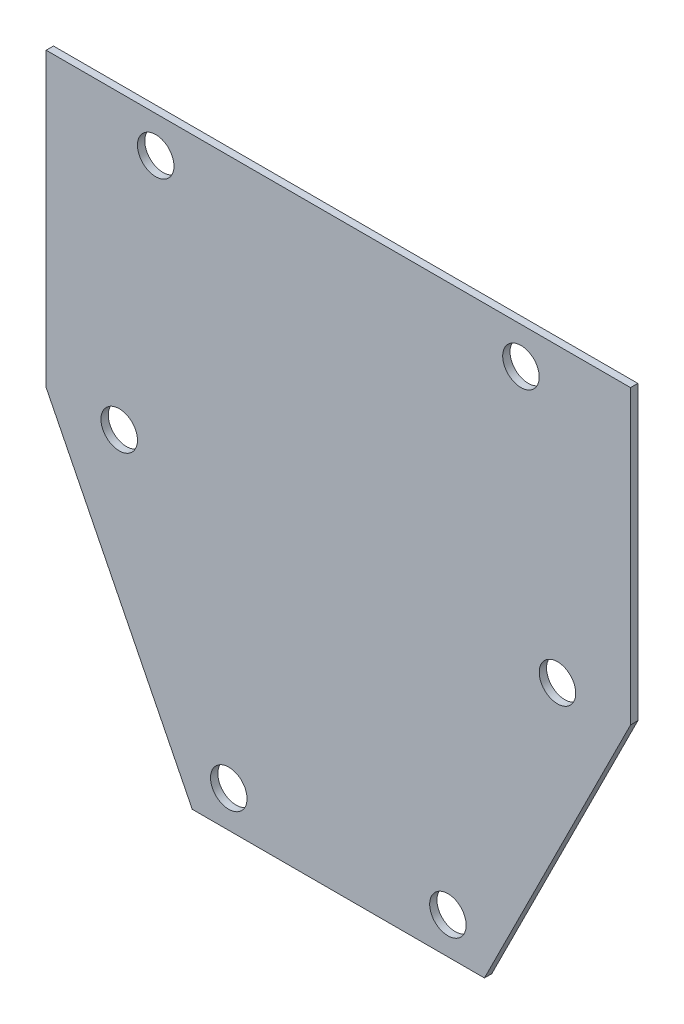
SolidWorks part; units mm, degrees
material "Plain Carbon Steel"
ref_plane "Front Plane" through (0, 0, 0) normal (0, 0, 1) x (1, 0, 0)
ref_plane "Top Plane" through (0, 0, 0) normal (0, 1, 0) x (1, 0, 0)
ref_plane "Right Plane" through (0, 0, 0) normal (1, 0, 0) x (0, 0, -1)
sketch "Sketch1" plane through (0, 0, 0) normal (0, 0, 1) x (1, 0, 0)
  line L0 (0, -40) -> (0, 40)
  line L1 (-40, -40) -> (40, -40)
  line L2 (-20, -40) -> (20, -40)
  line L3 (-20, -40) -> (-40, 0)
  line L4 (-40, 0) -> (-40, 40)
  line L5 (-40, 40) -> (40, 40)
  line L6 (40, 40) -> (40, 0)
  line L7 (40, 0) -> (20, -40)
  line L8 (0, -55) -> (0, 55) construction
  circle A0 centre (-30, 0) radius 2.5
  circle A1 centre (-25, 35) radius 2.5
  circle A2 centre (-15, -35) radius 2.5
  circle A3 centre (15, -35) radius 2.5
  circle A4 centre (30, 0) radius 2.5
  circle A5 centre (25, 35) radius 2.5
  point P4 (0, 0)
  point P8 (0, -40)
  point P10 (0, -40)
  dimension "D8" = 5
  dimension "D10" = 5
  dimension "D13" = 5
  dimension "D1" = 80
  dimension "D2" = 80
  dimension "D3" = 40
  dimension "D4" = 40
  dimension "D5" = 40
  dimension "D6" = 40
  dimension "D7" = 44.7214
  dimension "D9" = 10
  dimension "D11" = 5
  dimension "D12" = 15
  dimension "D14" = 5
  dimension "D15" = 55
  dimension "D16" = 40
extrude "Boss-Extrude1" add sketch "Sketch1" along normal mid plane 1 contours L7 L6 L5 L0 L1 A4 A3 A5 | L5 L4 L3 L1 L0 A2 A1 A0
